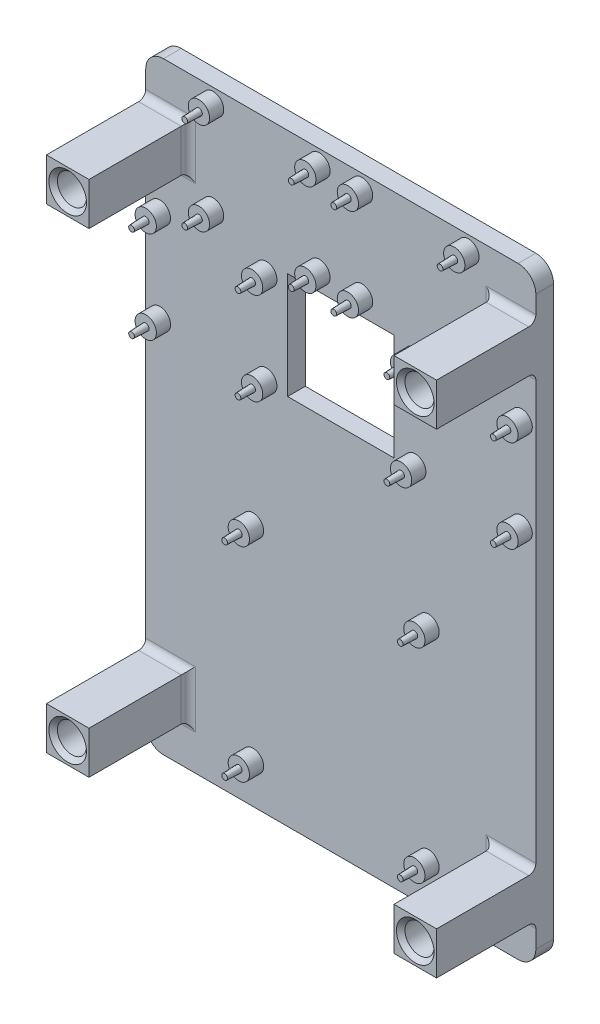
SolidWorks part; units mm, degrees
ref_plane "Ebene vorne" through (0, 0, 0) normal (0, 0, 1) x (1, 0, 0)
ref_plane "Ebene oben" through (0, 0, 0) normal (0, 1, 0) x (1, 0, 0)
ref_plane "Ebene rechts" through (0, 0, 0) normal (1, 0, 0) x (0, 0, -1)
sketch "Skizze1" plane through (0, 0, 0) normal (0, 0, 1) x (1, 0, 0)
  line L1 (-55, -85) -> (55, -85)
  line L2 (-55, -85) -> (-55, 85)
  line L3 (-55, 85) -> (55, 85)
  line L4 (55, -85) -> (55, 85)
  line L5 (-55, -85) -> (55, 85) construction
  line L6 (-55, 85) -> (55, -85) construction
  point P0 (0, 0)
  dimension "D1" = 110
  dimension "D2" = 170
extrude "Aufsatz-Linear austragen1" add sketch "Skizze1" along normal blind 5
fillet "Verrundung1" radius 5 4 edges at (-55, -85, 2.5) (55, -85, 2.5) (55, 85, 2.5) (-55, 85, 2.5)
sketch "Skizze7" plane through (0, 0, 5) normal (0, 0, 1) x (1, 0, 0)
  line L0 (-55, 80) -> (-55, -80) construction
  line L1 (-55, 73) -> (-43, 73)
  line L2 (-55, 73) -> (-55, 61)
  line L3 (-55, 61) -> (-43, 61)
  line L4 (-43, 73) -> (-43, 61)
  line L5 (50, 85) -> (-50, 85) construction
  line L18 (0, 85) -> (0, -85) construction
  line L19 (-50, -85) -> (50, -85) construction
  line L20 (-55, 0) -> (55, 0) construction
  line L21 (55, -80) -> (55, 80) construction
  line L22 (43, 73) -> (43, 61)
  line L23 (55, 61) -> (43, 61)
  line L24 (55, 73) -> (55, 61)
  line L25 (55, 73) -> (43, 73)
  line L26 (55, -73) -> (43, -73)
  line L27 (55, -73) -> (55, -61)
  line L28 (55, -61) -> (43, -61)
  line L29 (43, -73) -> (43, -61)
  line L30 (-43, -73) -> (-43, -61)
  line L31 (-55, -61) -> (-43, -61)
  line L32 (-55, -73) -> (-55, -61)
  line L33 (-55, -73) -> (-43, -73)
  dimension "D1" = 12
  dimension "D2" = 12
extrude "Aufsatz-Linear austragen3" add sketch "Skizze7" along normal blind 28
fillet "Verrundung2" radius 2 12 edges at (-49, 73, 5) (-49, 61, 5) (-43, 67, 5) (-49, -61, 5) (-43, -67, 5) (-49, -73, 5) (49, -73, 5) (43, -67, 5) (49, -61, 5) (49, 61, 5) (43, 67, 5) (49, 73, 5)
sketch "Skizze8" plane through (0, 0, 33) normal (0, 0, 1) x (1, 0, 0)
  line L0 (-55, 73) -> (-43, 61) construction
  line L1 (-55, 61) -> (-43, 73) construction
  line L5 (-55, 31.954) -> (-55, -16.1316) construction
  line L8 (-55, 59) -> (-55, -59) construction
  circle A1 centre (-49, 67) radius 4.1
  dimension "D1" = 8.2
extrude "Schnitt-Linear austragen3" cut sketch "Skizze8" against normal through all
pattern_linear "Lineares Muster1" count 2 spacing 134 along (0, -1, 0) count 2 spacing 98 along (1, 0, 0) of "Schnitt-Linear austragen3"
sketch "Skizze9" plane through (0, 0, 5) normal (0, 0, 1) x (1, 0, 0)
  line L0 (0, 85) -> (0, -85) construction
  line L1 (-28, -77) -> (28, -77) construction
  line L2 (-28, -77) -> (-28, 12) construction
  line L3 (-28, 12) -> (28, 12) construction
  line L4 (28, -77) -> (28, 12) construction
  line L5 (-28, -77) -> (28, 12) construction
  line L6 (-28, 12) -> (28, -77) construction
  line L11 (50, 85) -> (-50, 85) construction
  line L12 (-50, -85) -> (50, -85) construction
  line L13 (-55, 59) -> (-55, -59) construction
  line L14 (-51, 21) -> (-21, 21) construction
  line L15 (-51, 21) -> (-51, 47) construction
  line L16 (-51, 47) -> (-21, 47) construction
  line L17 (-21, 21) -> (-21, 47) construction
  line L18 (-51, 21) -> (-21, 47) construction
  line L19 (-51, 47) -> (-21, 21) construction
  line L21 (-36, 55) -> (-6, 55) construction
  line L22 (-36, 55) -> (-36, 81) construction
  line L23 (-36, 81) -> (-6, 81) construction
  line L24 (-6, 55) -> (-6, 81) construction
  line L25 (-36, 55) -> (-6, 81) construction
  line L26 (-36, 81) -> (-6, 55) construction
  line L27 (51, 47) -> (21, 47) construction
  line L28 (21, 21) -> (21, 47) construction
  line L29 (51, 21) -> (21, 21) construction
  line L30 (51, 21) -> (51, 47) construction
  line L31 (36, 81) -> (6, 81) construction
  line L32 (6, 55) -> (6, 81) construction
  line L33 (36, 55) -> (6, 55) construction
  line L34 (36, 55) -> (36, 81) construction
  circle A0 centre (24.75, -73.75) radius 3
  circle A1 centre (24.75, -16.25) radius 3
  circle A2 centre (-24.75, -16.25) radius 3
  circle A3 centre (-24.75, -73.75) radius 3
  circle A4 centre (-36, 81) radius 3
  circle A5 centre (-6, 81) radius 3
  circle A6 centre (-36, 55) radius 3
  circle A7 centre (-6, 55) radius 3
  circle A8 centre (6, 81) radius 3
  circle A9 centre (36, 81) radius 3
  circle A10 centre (36, 55) radius 3
  circle A11 centre (6, 55) radius 3
  circle A12 centre (21, 47) radius 3
  circle A13 centre (51, 47) radius 3
  circle A14 centre (51, 21) radius 3
  circle A15 centre (21, 21) radius 3
  circle A16 centre (-21, 47) radius 3
  circle A17 centre (-51, 47) radius 3
  circle A18 centre (-51, 21) radius 3
  circle A19 centre (-21, 21) radius 3
  point P0 (0, 0)
  point P5 (0, -32.5)
  point P21 (-36, 34)
  point P28 (-21, 68)
  dimension "D3" = 3.25
  dimension "D4" = 6
  dimension "D5" = 57.5
  dimension "D17" = 6
  dimension "D1" = 56
  dimension "D2" = 89
  dimension "D6" = 3.25
  dimension "D7" = 8
  dimension "D8" = 28
  dimension "D9" = 26
  dimension "D10" = 30
  dimension "D11" = 4
  dimension "D12" = 38
  dimension "D13" = 26
  dimension "D14" = 30
  dimension "D15" = 4
  dimension "D16" = 19
extrude "Aufsatz-Linear austragen4" add sketch "Skizze9" along normal blind 4
sketch "Skizze10" plane through (0, 0, 9) normal (0, 0, 1) x (1, 0, 0)
  line L0 (0, -85) -> (0, 85) construction
  line L1 (-50, -85) -> (50, -85) construction
  line L2 (50, 85) -> (-50, 85) construction
  circle A0 centre (24.75, -73.75) radius 0.95
  circle A1 centre (24.75, -16.25) radius 0.95
  circle A2 centre (-24.75, -16.25) radius 0.95
  circle A3 centre (-24.75, -73.75) radius 0.95
  circle A4 centre (-51, 47) radius 0.95
  circle A5 centre (-51, 21) radius 0.95
  circle A6 centre (-21, 21) radius 0.95
  circle A7 centre (-21, 47) radius 0.95
  circle A8 centre (-36, 55) radius 0.95
  circle A9 centre (-6, 55) radius 0.95
  circle A10 centre (6, 55) radius 0.95
  circle A11 centre (-36, 81) radius 0.95
  circle A12 centre (-6, 81) radius 0.95
  circle A13 centre (6, 81) radius 0.95
  circle A14 centre (36, 81) radius 0.95
  circle A15 centre (36, 55) radius 0.95
  circle A16 centre (21, 47) radius 0.95
  circle A17 centre (51, 47) radius 0.95
  circle A18 centre (21, 21) radius 0.95
  circle A19 centre (51, 21) radius 0.95
  dimension "D1" = 1.9
extrude "Aufsatz-Linear austragen5" add sketch "Skizze10" along normal blind 4 draft 2
chamfer "Fase1" distance 1.2 angle 45 4 edges at (-44.9, 67, 33) (-44.9, -67, 33) (53.1, -67, 33) (53.1, 67, 33)
sketch "Skizze11" plane through (0, 0, 5) normal (0, 0, 1) x (1, 0, 0)
  line L0 (0, 85) -> (0, -85) construction
  line L1 (-15, 20) -> (15, 20)
  line L2 (-15, 20) -> (-15, 50)
  line L3 (-15, 50) -> (15, 50)
  line L4 (15, 20) -> (15, 50)
  line L5 (-15, 20) -> (15, 50) construction
  line L6 (-15, 50) -> (15, 20) construction
  line L7 (50, 85) -> (-50, 85) construction
  line L8 (-50, -85) -> (50, -85) construction
  point P0 (0, 35)
  point P11 (0, 0)
  point P12 (0, 0)
  dimension "D1" = 30
  dimension "D2" = 30
  dimension "D3" = 35
extrude "Schnitt-Linear austragen4" cut sketch "Skizze11" against normal through all
